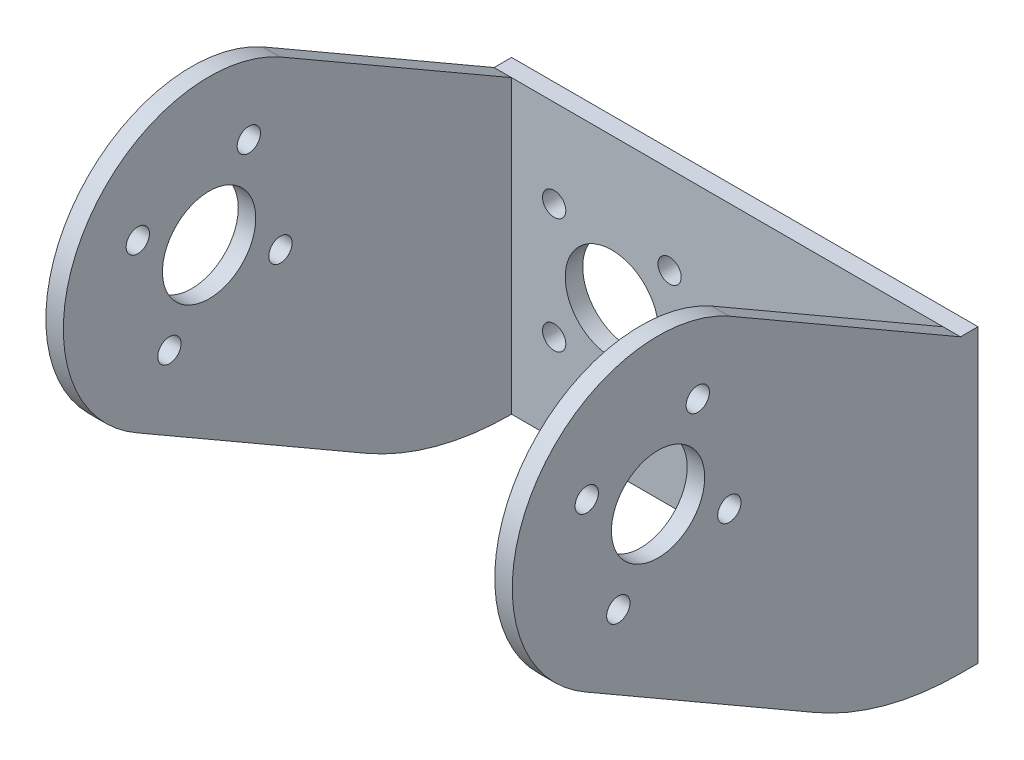
SolidWorks part; units mm, degrees
ref_plane "Front Plane" through (0, 0, 0) normal (0, 0, 1) x (1, 0, 0)
ref_plane "Top Plane" through (0, 0, 0) normal (0, 1, 0) x (1, 0, 0)
ref_plane "Right Plane" through (0, 0, 0) normal (1, 0, 0) x (0, 0, -1)
sketch "Sketch3" plane through (0, 0, 0) normal (0, 1, 0) x (1, 0, 0)
  line L1 (-16.8274, 0) -> (23.1726, 0)
  line L2 (-16.8274, 0) -> (-16.8274, -1.5)
  line L3 (-16.8274, -1.5) -> (23.1726, -1.5)
  line L4 (23.1726, 0) -> (23.1726, -1.5)
  dimension "D1" = 40
  dimension "D2" = 1.5
extrude "Boss-Extrude3" add sketch "Sketch3" along normal blind 25
sketch "Sketch4" plane through (23.1726, 0, 0) normal (1, 0, 0) x (0, 0, -1)
  line L0 (-1.5, 25) -> (-14, 3.3494) construction
  line L1 (-14, 3.3494) -> (-33.5222, 14.6205)
  line L2 (-1.5, 25) -> (-21.3551, 36.4634)
  line L3 (-1.5, 25) -> (-1.5, 0) construction
  line L4 (-1.5, 0) -> (0, 0) construction
  line L5 (-33.5222, 14.6205) -> (-21.3551, 36.4634) construction
  line L6 (-1.5, 0) -> (-1.5, 25)
  arc A0 (-14, 3.3494) -> (-1.5, 0) centre (-1.5, 25) ccw
  arc A1 (-21.3551, 36.4634) -> (-33.5222, 14.6205) centre (-27.4387, 25.5419) ccw
  circle A2 centre (-27.4387, 25.5419) radius 4
  circle A3 centre (-30.845, 19.4267) radius 1
  circle A4 centre (-33.5539, 28.9483) radius 1
  circle A5 centre (-24.0323, 31.6572) radius 1
  circle A6 centre (-21.3234, 22.1356) radius 1
  point P24 (-27.4387, 25.5419)
  line M7 (-1.5, 25) -> (-1.5, 0)
  dimension "D5" = 8
  dimension "D6" = 2
  dimension "D1" = 25
  dimension "D2" = 30
  dimension "D3" = 90
  dimension "D4" = 90
  dimension "D7" = 7
  dimension "D8" = 4
extrude "Boss-Extrude4" add sketch "Sketch4" against normal blind 1.5 contours L2 A1 L1 A0 M7
ref_plane "Plane1" through (3.1726, 0, 0) normal (-1, 0, 0) x (0, 0, 1)
mirror "Mirror1" about plane through (3.1726, 0, 0) normal (-1, 0, 0) of "Boss-Extrude4"
sketch "Sketch5" plane through (23.1726, 0, 0) normal (1, 0, 0) x (0, 0, -1)
sketch "Sketch6" plane through (0, 0, 0) normal (0, 0, -1) x (-1, 0, 0)
  line L0 (-3.1726, -0.825) -> (-3.1726, 0.825) construction
  line L1 (-23.1726, 0) -> (16.8274, 0) construction
  line L2 (-8.1224, 7.5503) -> (-3.1726, 12.5) construction
  line L3 (-3.1726, 12.5) -> (-13.0721, 12.5) construction
  line L4 (-8.1224, 7.5503) -> (-13.0721, 12.5) construction
  line L5 (-3.1726, 12.5) -> (-3.1726, 0) construction
  circle A0 centre (-3.1726, 12.5) radius 4
  circle A1 centre (-13.0721, 12.5) radius 4
  circle A2 centre (-8.1224, 7.5503) radius 1
  circle A6 centre (-18.0219, 7.5503) radius 1
  circle A7 centre (-18.0219, 17.4497) radius 1
  circle A8 centre (-8.1224, 17.4497) radius 1
  circle A9 centre (11.6766, 17.4497) radius 1
  circle A10 centre (1.7771, 17.4497) radius 1
  circle A11 centre (11.6766, 7.5503) radius 1
  circle A12 centre (6.7269, 12.5) radius 4
  circle A13 centre (1.7771, 7.5503) radius 1
  point P19 (-13.8657, 12.5)
  point P20 (-13.0721, 12.5)
  dimension "D1" = 8
  dimension "D2" = 8
  dimension "D3" = 2
  dimension "D4" = 7
  dimension "D5" = 7
  dimension "D6" = 12.5
  dimension "D8" = 45
  dimension "D7" = 4
extrude "Cut-Extrude1" cut sketch "Sketch6" against normal blind 1.5
